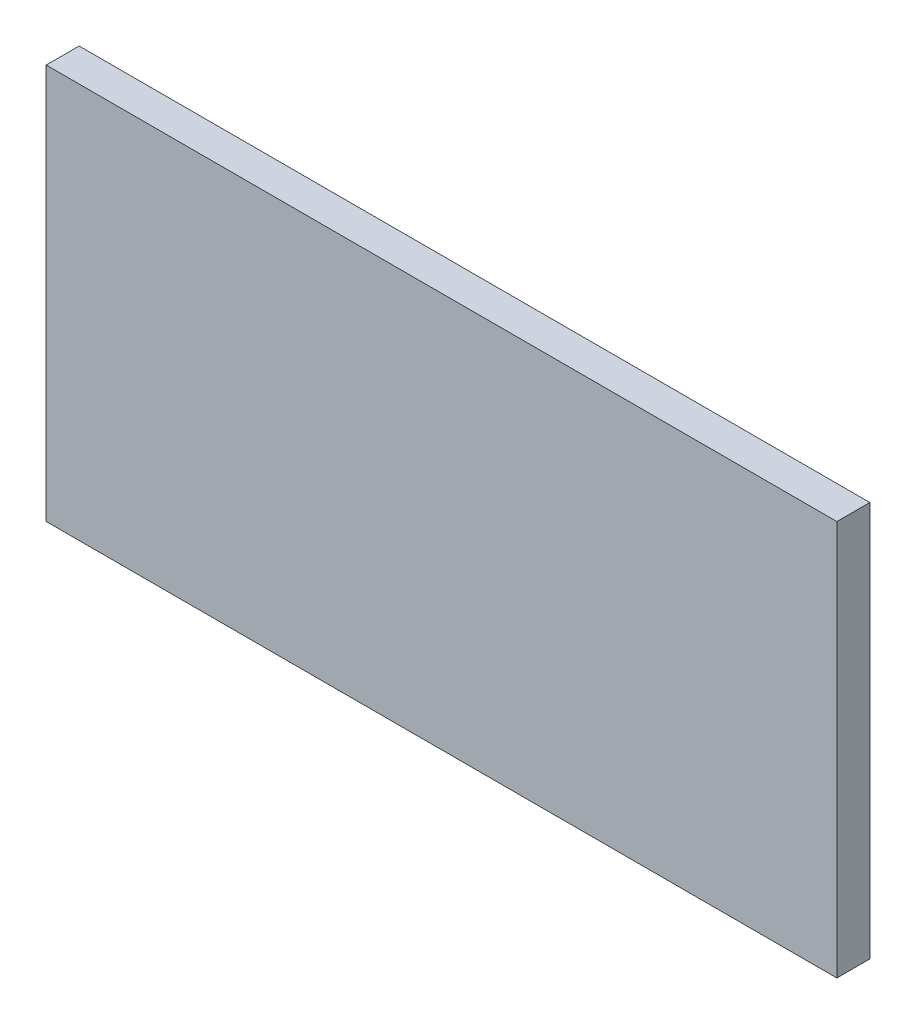
SolidWorks part; units mm, degrees
ref_plane "Front Plane" through (0, 0, 0) normal (0, 0, 1) x (1, 0, 0)
ref_plane "Top Plane" through (0, 0, 0) normal (0, 1, 0) x (1, 0, 0)
ref_plane "Right Plane" through (0, 0, 0) normal (1, 0, 0) x (0, 0, -1)
sketch "Sketch1" plane through (0, 0, 0) normal (0, 0, 1) x (1, 0, 0)
  line L1 (0, 0) -> (120, 0)
  line L2 (0, 0) -> (0, -60)
  line L3 (0, -60) -> (120, -60)
  line L4 (120, 0) -> (120, -60)
  dimension "D1" = 60
  dimension "D2" = 120
extrude "Boss-Extrude1" add sketch "Sketch1" along normal blind 5
